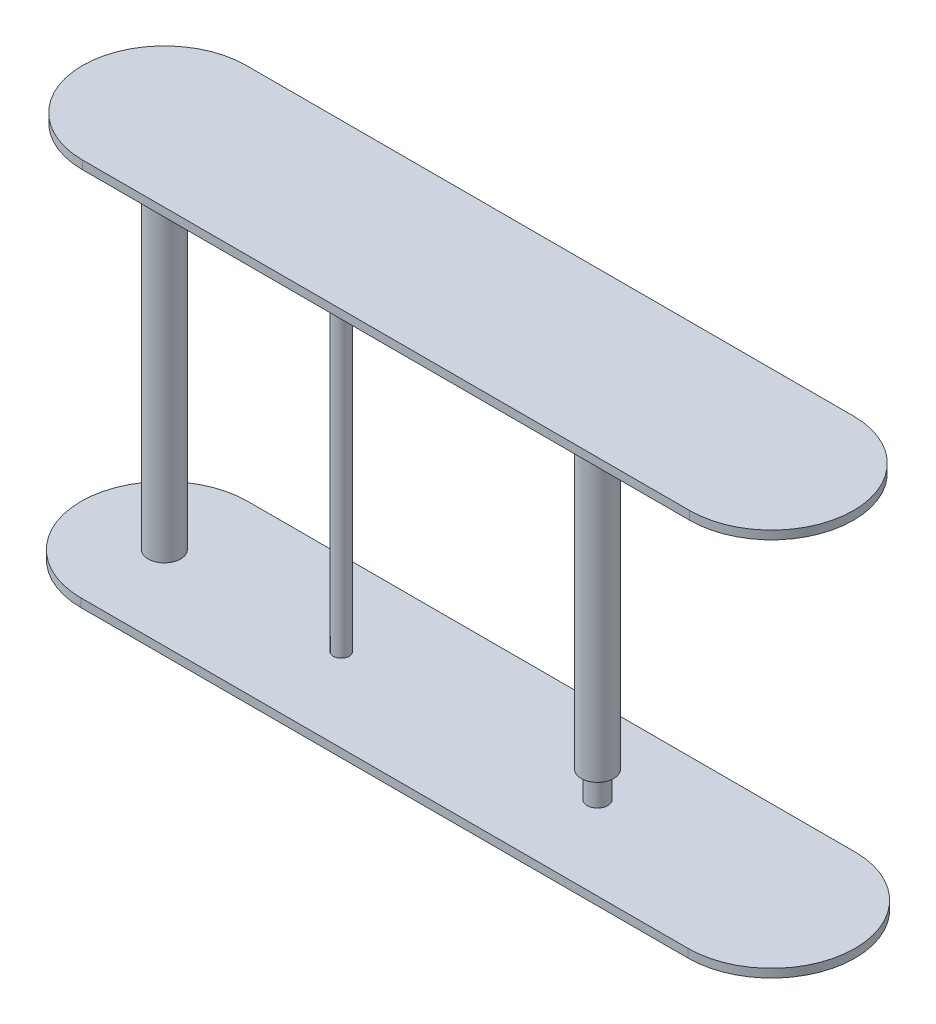
SolidWorks part; units mm, degrees
ref_plane "Front Plane" through (0, 0, 0) normal (0, 0, 1) x (1, 0, 0)
ref_plane "Top Plane" through (0, 0, 0) normal (0, 1, 0) x (1, 0, 0)
ref_plane "Right Plane" through (0, 0, 0) normal (1, 0, 0) x (0, 0, -1)
sketch "Sketch1" plane through (0, 0, 0) normal (0, 1, 0) x (1, 0, 0)
  line L0 (-110.5891, 0) -> (119.2109, 0) construction
  line L1 (-110.5891, 31.6) -> (119.2109, 31.6)
  line L2 (-110.5891, -31.6) -> (119.2109, -31.6)
  arc A0 (-110.5891, 31.6) -> (-110.5891, -31.6) centre (-110.5891, 0) ccw
  arc A1 (119.2109, -31.6) -> (119.2109, 31.6) centre (119.2109, 0) ccw
  point P3 (4.3109, 0)
  point P8 (-142.1891, 0)
  point P9 (150.8109, 0)
  dimension "D1" = 63.2
  dimension "D2" = 293
extrude "Boss-Extrude1" add sketch "Sketch1" along normal blind 3.2
ref_plane "Plane4" through (0, 143.2, 0) normal (0, 1, 0) x (1, 0, 0)
sketch "Sketch8" plane through (0, 3.2, 0) normal (0, 1, 0) x (1, 0, 0)
  line L0 (-110.5891, 31.6) -> (-110.5891, -31.6) construction
  line L1 (-142.1891, 0) -> (150.8109, 0) construction
  arc A0 (-110.5891, 31.6) -> (-110.5891, -31.6) centre (-110.5891, 0) ccw construction
  arc A1 (119.2109, -31.6) -> (119.2109, 31.6) centre (119.2109, 0) ccw construction
  circle A2 centre (-110.5891, 0) radius 6.15
  dimension "D1" = 12.3
extrude "Boss-Extrude5" add sketch "Sketch8" along normal blind 140
sketch "Sketch11" plane through (0, 143.2, 0) normal (0, 1, 0) x (1, 0, 0)
  line L0 (-142.1891, 0) -> (150.8109, 0) construction
  line L3 (119.2109, 31.6) -> (119.2109, -31.6) construction
  line L4 (-110.5891, 31.6) -> (-110.5891, -31.6) construction
  line L5 (4.3109, 31.6) -> (4.3109, -31.6) construction
  line L6 (119.2109, 31.6) -> (-110.5891, 31.6) construction
  line L7 (-110.5891, -31.6) -> (119.2109, -31.6) construction
  line L8 (-110.5891, 0) -> (119.2109, 0) construction
  line L9 (-110.5891, 30.9882) -> (119.2109, 30.9882)
  line L10 (-110.5891, -30.9882) -> (119.2109, -30.9882)
  arc A2 (-110.5891, 31.6) -> (-110.5891, -31.6) centre (-110.5891, 0) ccw construction
  arc A3 (119.2109, -31.6) -> (119.2109, 31.6) centre (119.2109, 0) ccw construction
  arc A4 (-110.5891, 30.9882) -> (-110.5891, -30.9882) centre (-110.5891, 0) ccw
  arc A5 (119.2109, -30.9882) -> (119.2109, 30.9882) centre (119.2109, 0) ccw
  point P24 (4.3109, 0)
extrude "Boss-Extrude6" add sketch "Sketch11" along normal blind 3.2
sketch "Sketch12" plane through (0, 3.2, 0) normal (0, 1, 0) x (1, 0, 0)
  line L0 (-141.5773, 0) -> (150.8109, 0) construction
  line L1 (-110.5891, 31.6) -> (-110.5891, -30.9882) construction
  line L2 (-43.6391, 31.6) -> (-43.6391, -31.6) construction
  line L3 (119.2109, 31.6) -> (-110.5891, 31.6) construction
  line L4 (-110.5891, -31.6) -> (119.2109, -31.6) construction
  arc A0 (-110.5891, 30.9882) -> (-110.5891, -30.9882) centre (-110.5891, 0) ccw construction
  arc A1 (119.2109, -31.6) -> (119.2109, 31.6) centre (119.2109, 0) ccw construction
  circle A2 centre (-43.6391, 0) radius 3
  dimension "D1" = 6
  dimension "D2" = 66.95
extrude "Boss-Extrude7" add sketch "Sketch12" along normal blind 140
sketch "Sketch14" plane through (0, 3.2, 0) normal (0, 1, 0) x (1, 0, 0)
  line L0 (-141.5773, 0) -> (150.1991, 0) construction
  line L1 (53.3109, 30.9882) -> (53.3109, -30.9882) construction
  line L2 (119.2109, 30.9882) -> (-110.5891, 30.9882) construction
  line L3 (-110.5891, -30.9882) -> (119.2109, -30.9882) construction
  line L4 (-110.5891, 30.9882) -> (-110.5891, -31.6) construction
  arc A0 (-110.5891, 30.9882) -> (-110.5891, -30.9882) centre (-110.5891, 0) ccw construction
  arc A1 (119.2109, -30.9882) -> (119.2109, 30.9882) centre (119.2109, 0) ccw construction
  circle A2 centre (53.3109, 0) radius 3.9
  dimension "D2" = 7.8
  dimension "D1" = 163.9
extrude "Boss-Extrude8" add sketch "Sketch14" along normal blind 10
sketch "Sketch15" plane through (0, 13.2, 0) normal (0, 1, 0) x (1, 0, 0)
  circle A0 centre (53.3109, 0) radius 6.15
  dimension "D1" = 12.3
extrude "Boss-Extrude9" add sketch "Sketch15" along normal blind 60
ref_plane "Plane6" through (0, 73.2, 0) normal (0, 1, 0) x (1, 0, 0)
mirror "Mirror7" about plane through (0, 73.2, 0) normal (0, 1, 0) of "Boss-Extrude8", "Boss-Extrude9"
